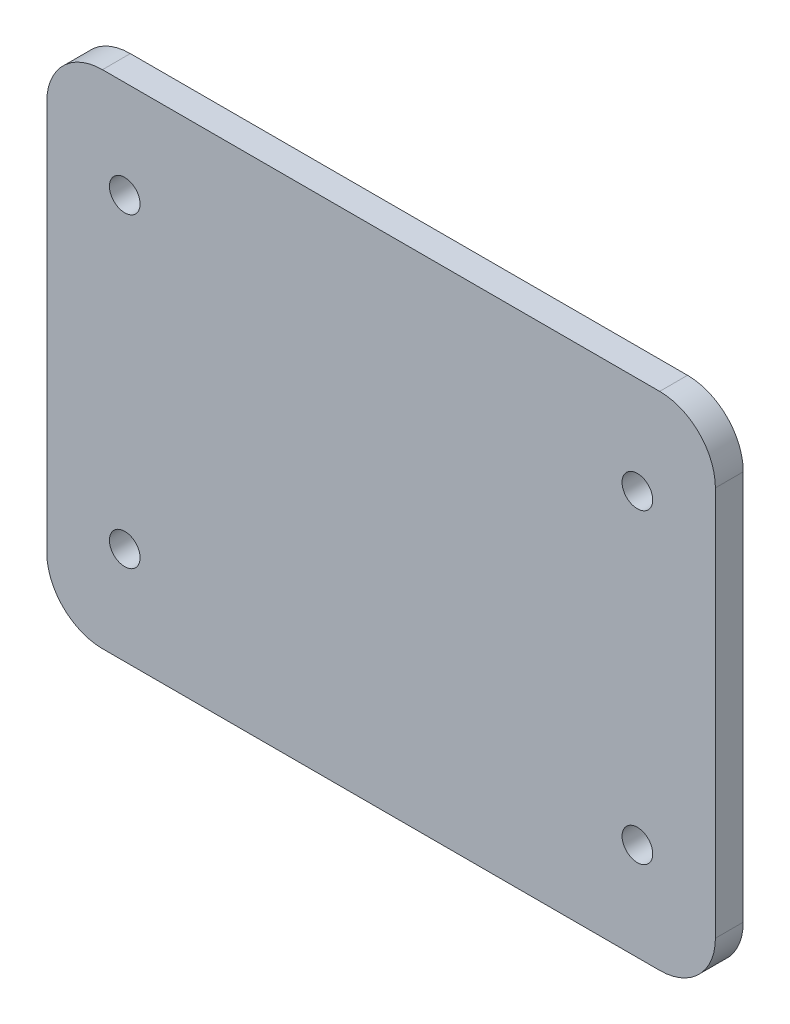
SolidWorks part; units mm, degrees
ref_plane "前视基准面" through (0, 0, 0) normal (0, 0, 1) x (1, 0, 0)
ref_plane "上视基准面" through (0, 0, 0) normal (0, 1, 0) x (1, 0, 0)
ref_plane "右视基准面" through (0, 0, 0) normal (1, 0, 0) x (0, 0, -1)
sketch "草图1" plane through (0, 0, 0) normal (0, 0, 1) x (1, 0, 0)
  line L0 (65.1489, 28.2128) -> (65.1489, 10.7128)
  line L1 (-40.8511, 28.2128) -> (79.1489, 28.2128)
  line L2 (-40.8511, 28.2128) -> (-40.8511, -61.7872)
  line L3 (-40.8511, -61.7872) -> (79.1489, -61.7872)
  line L4 (79.1489, 28.2128) -> (79.1489, -61.7872)
  line L5 (65.1489, -61.7872) -> (65.1489, -44.2872)
  line L6 (65.1489, 28.2128) -> (79.1489, 28.2128)
  line L7 (65.1489, -61.7872) -> (79.1489, -61.7872)
  line L8 (-40.8511, 28.2128) -> (79.1489, -61.7872)
  line L9 (79.1489, 28.2128) -> (-40.8511, -61.7872)
  line L10 (19.1489, -16.7872) -> (19.1489, -2.4712)
  line L11 (19.1489, 28.2128) -> (19.1489, -61.7872)
  circle A0 centre (65.1489, 10.7128) radius 2.75
  circle A1 centre (65.1489, -44.2872) radius 2.75
  circle A2 centre (-26.8511, -44.2872) radius 2.75
  circle A3 centre (-26.8511, 10.7128) radius 2.75
  dimension "D1" = 120
  dimension "D2" = 90
  dimension "D3" = 17.5
  dimension "D4" = 17.5
  dimension "D5" = 14
  dimension "D6" = 14
extrude "凸台-拉伸1" add sketch "草图1" along normal blind 5
fillet "圆角1" radius 10 4 edges at (79.1489, 28.2128, 2.5) (-40.8511, 28.2128, 2.5) (-40.8511, -61.7872, 2.5) (79.1489, -61.7872, 2.5)
